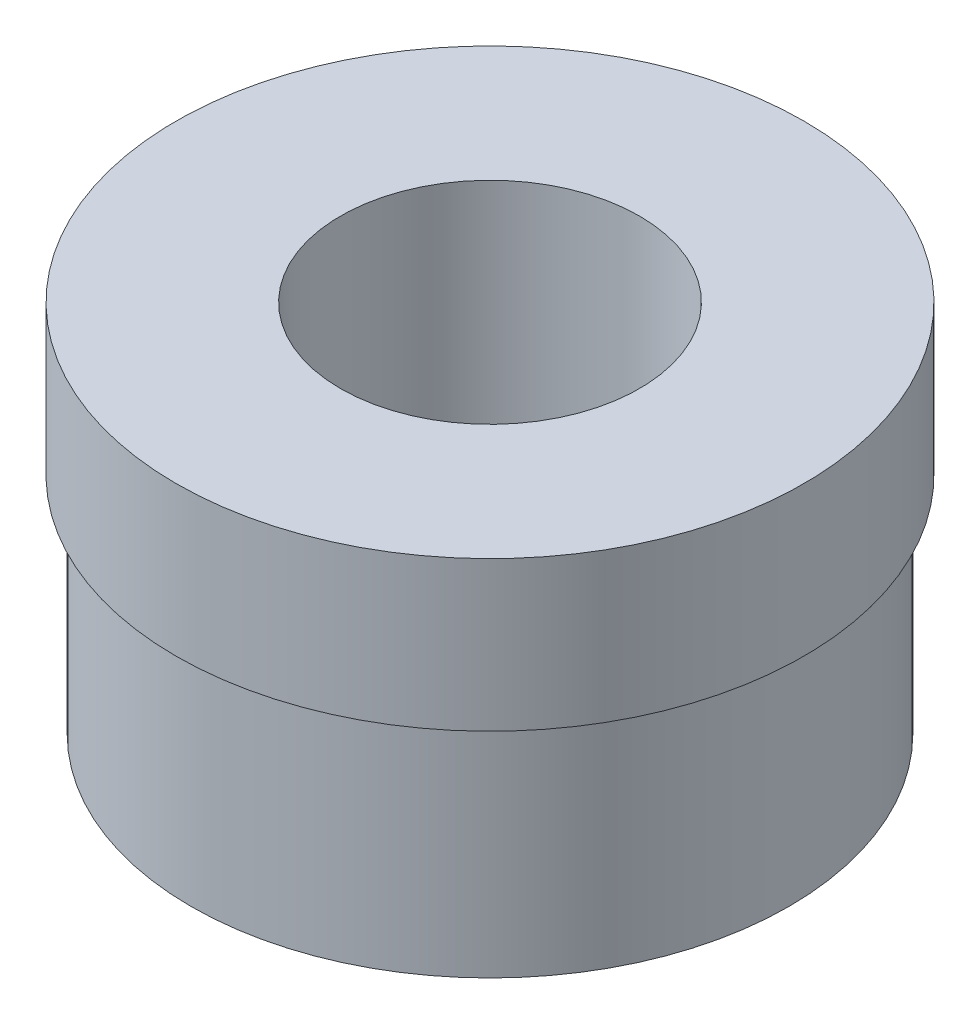
SolidWorks part; units mm, degrees
material "Plain Carbon Steel"
ref_plane "Front Plane" through (0, 0, 0) normal (0, 0, 1) x (1, 0, 0)
ref_plane "Top Plane" through (0, 0, 0) normal (0, 1, 0) x (1, 0, 0)
ref_plane "Right Plane" through (0, 0, 0) normal (1, 0, 0) x (0, 0, -1)
sketch "Sketch1" plane through (0, 0, 0) normal (0, 0, 1) x (1, 0, 0)
  line L0 (0, 61.8349) -> (0, -68.8073) construction
  line L1 (10, 0) -> (10, 25)
  line L2 (21, 25) -> (21, 15)
  line L3 (21, 15) -> (20, 15)
  line L4 (20, 15) -> (20, 0)
  line L5 (20, 0) -> (10, 0)
  line L6 (10, 25) -> (21, 25)
  dimension "D1" = 20
  dimension "D2" = 40
  dimension "D3" = 25
  dimension "D4" = 10
  dimension "D5" = 42
revolve "Revolve1" add sketch "Sketch1" angle 360 about L0
ref_plane "Center" through (0, 12.5, 0) normal (0, -1, 0) x (-1, 0, 0)
